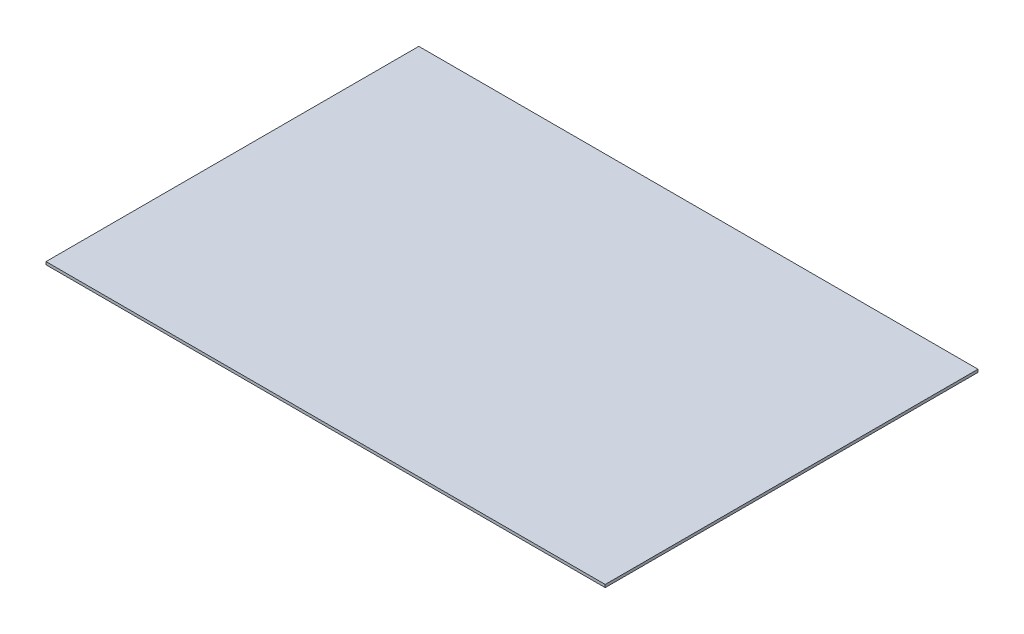
SolidWorks part; units mm, degrees
ref_plane "Front Plane" through (0, 0, 0) normal (0, 0, 1) x (1, 0, 0)
ref_plane "Top Plane" through (0, 0, 0) normal (0, 1, 0) x (1, 0, 0)
ref_plane "Right Plane" through (0, 0, 0) normal (1, 0, 0) x (0, 0, -1)
sketch "Sketch1" plane through (0, 0, 0) normal (0, 1, 0) x (1, 0, 0)
  line L1 (0, 0) -> (300, 0)
  line L2 (0, 0) -> (0, 200)
  line L3 (0, 200) -> (300, 200)
  line L4 (300, 0) -> (300, 200)
  dimension "D1" = 200
  dimension "D2" = 300
extrude "Boss-Extrude1" add sketch "Sketch1" along normal blind 1.5
